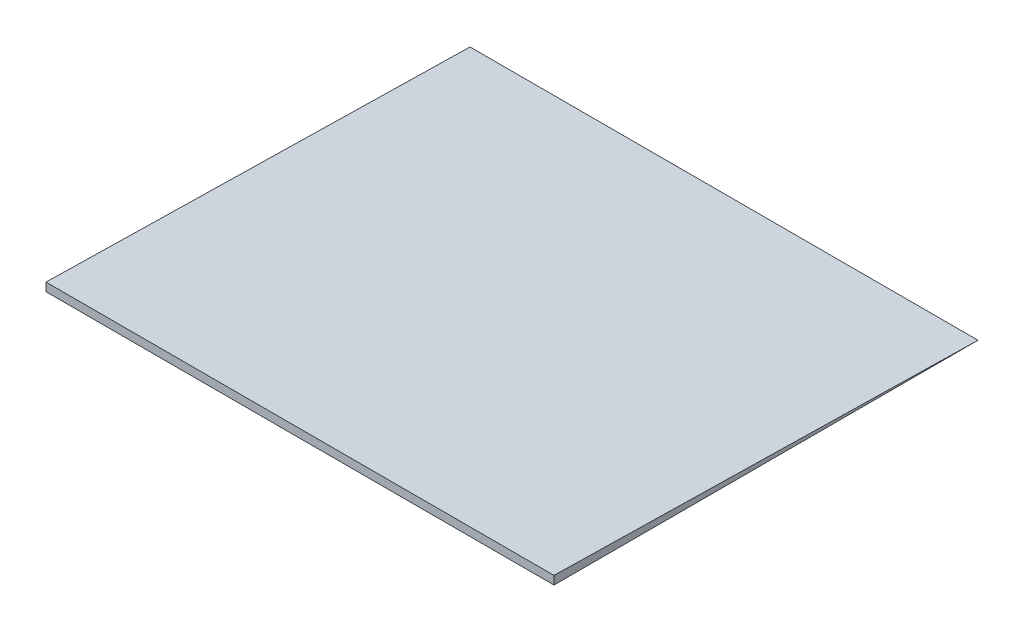
SolidWorks part; units mm, degrees
ref_plane "Front Plane" through (0, 0, 0) normal (0, 0, 1) x (1, 0, 0)
ref_plane "Top Plane" through (0, 0, 0) normal (0, 1, 0) x (1, 0, 0)
ref_plane "Right Plane" through (0, 0, 0) normal (1, 0, 0) x (0, 0, -1)
sketch "Sketch1" plane through (0, 0, 0) normal (0, 1, 0) x (1, 0, 0)
  line L1 (91, 75.955) -> (-91, 75.955)
  line L2 (91, 75.955) -> (91, -75.955)
  line L3 (91, -75.955) -> (-91, -75.955)
  line L4 (-91, 75.955) -> (-91, -75.955)
  line L5 (91, 75.955) -> (-91, -75.955) construction
  line L6 (91, -75.955) -> (-91, 75.955) construction
  point P0 (0, 0)
  dimension "D1" = 182
  dimension "D2" = 151.91
extrude "Boss-Extrude1" add sketch "Sketch1" along normal blind 3
sketch "Sketch2" plane through (91, 0, 0) normal (1, 0, 0) x (0, 0, -1)
  line L0 (-75.955, 3) -> (75.955, 3)
  line L1 (75.955, 3) -> (75.955, 0)
  line L2 (75.955, 0) -> (-75.955, 3)
extrude "Cut-Extrude1" cut sketch "Sketch2" against normal through all
